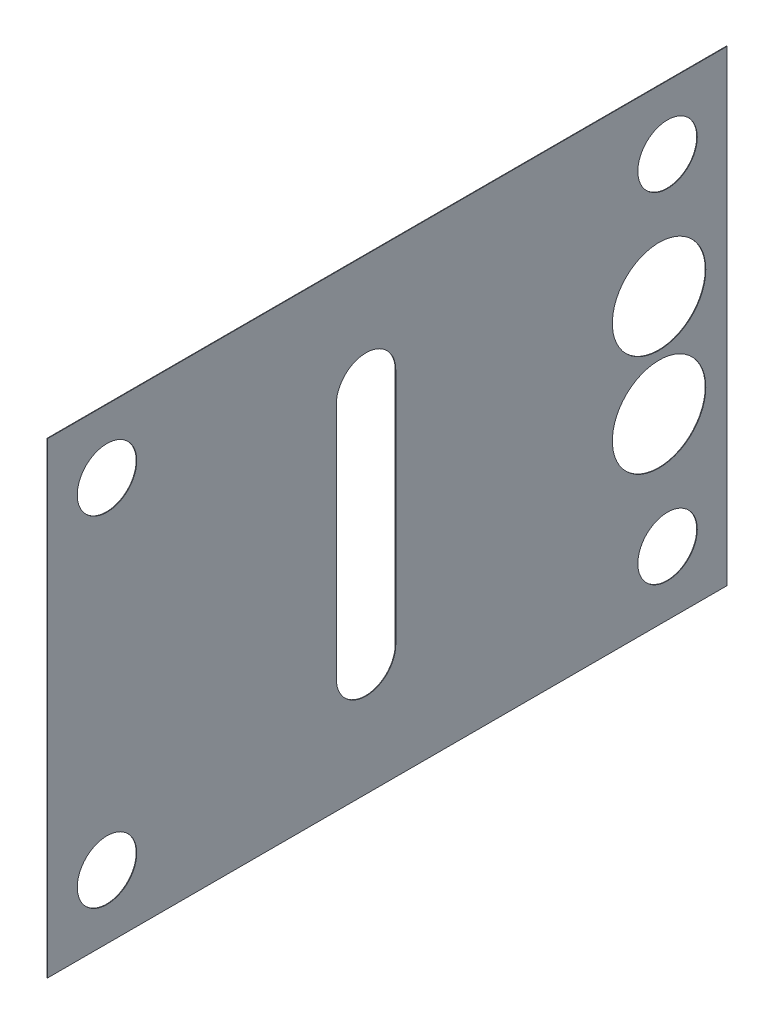
SolidWorks part; units mm, degrees
material "Low Carbon Steel"
ref_plane "Front Plane" through (0, 0, 0) normal (0, 0, 1) x (1, 0, 0)
ref_plane "Top Plane" through (0, 0, 0) normal (0, 1, 0) x (1, 0, 0)
ref_plane "Right Plane" through (0, 0, 0) normal (1, 0, 0) x (0, 0, -1)
sketch "Sketch1" plane through (0, 0, 0) normal (1, 0, 0) x (0, 0, -1)
  line L0 (-80, -55) -> (80, 55) construction
  line L1 (-80, 55) -> (80, 55)
  line L2 (-80, 55) -> (-80, -55)
  line L3 (-80, -55) -> (80, -55)
  line L4 (80, 55) -> (80, -55)
  dimension "D1" = 160
  dimension "D2" = 110
extrude "Boss-Extrude1" add sketch "Sketch1" along normal blind 0.127
hole_wizard "M12 Clearance Hole1" positions "Sketch2" profile "Sketch3" hole size "M12" standard "Peddi DIN" end condition through all
sketch "Sketch2" plane through (0.127, 0, 0) normal (1, 0, 0) x (0, 0, -1)
  line L0 (-66, 40) -> (66, 40) construction
  line L1 (66, 40) -> (66, -40) construction
  line L2 (66, -40) -> (-66, -40) construction
  line L3 (-66, -40) -> (66, 40) construction
  point P0 (-66, 40)
  point P2 (66, 40)
  point P4 (66, -40)
  point P6 (-66, -40)
  dimension "D1" = 80
  dimension "D2" = 132
sketch "Sketch3" plane through (0.127, 40, 66) normal (0, 1, 0) x (0, 0, -1)
  line L0 (0, 0) -> (0, 0.127)
  line L1 (0, 0.127) -> (7, 0.127)
  line L2 (7, 0.127) -> (7, 0)
  line L5 (7, 0) -> (0, 0)
  line L11 (0, -6.35) -> (0, 107.95) construction
  dimension "Thru Hole Dia." = 14
  dimension "Thru Hole Depth" = 0.127
sketch "Sketch4" plane through (0.127, 0, 0) normal (1, 0, 0) x (0, 0, -1)
  line L0 (-5, 28) -> (-5, -28) construction
  line L1 (2, 28) -> (2, -28)
  line L2 (-12, 28) -> (-12, -28)
  line L3 (-5, 0) -> (0, 0) construction
  arc A0 (2, 28) -> (-12, 28) centre (-5, 28) ccw
  arc A1 (-12, -28) -> (2, -28) centre (-5, -28) ccw
  circle A2 centre (66, 40) radius 7 construction
  point P2 (-5, 0)
  dimension "D3" = 71
  dimension "D1" = 14
  dimension "D2" = 56
extrude "Cut-Extrude1" cut sketch "Sketch4" against normal through all
hole_wizard "M20 Clearance Hole1" positions "Sketch5" profile "Sketch6" hole size "M20" standard "Peddi DIN" end condition through all
sketch "Sketch5" plane through (0.127, 0, 0) normal (1, 0, 0) x (0, 0, -1)
  line L0 (64, 12) -> (64, -12) construction
  line L2 (0, 0) -> (64, 0) construction
  circle A0 centre (66, 40) radius 7 construction
  point P0 (64, 12)
  point P5 (64, -12)
  dimension "D2" = 2
  dimension "D1" = 28
sketch "Sketch6" plane through (0.127, 12, -64) normal (0, 1, 0) x (0, 0, -1)
  line L0 (0, 0) -> (0, 0.127)
  line L1 (0, 0.127) -> (11, 0.127)
  line L2 (11, 0.127) -> (11, 0)
  line L5 (11, 0) -> (0, 0)
  line L11 (0, -6.35) -> (0, 107.95) construction
  dimension "Thru Hole Dia." = 22
  dimension "Thru Hole Depth" = 0.127
other "Freeze***"
